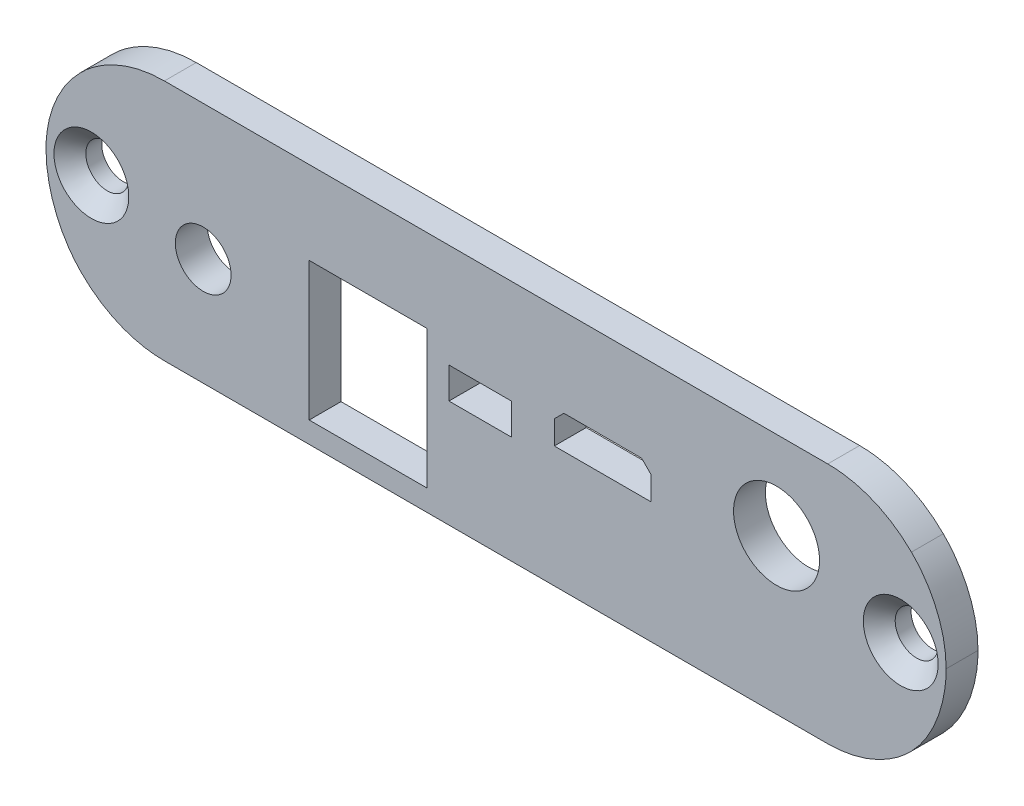
SolidWorks part; units mm, degrees
ref_plane "Front Plane" through (0, 0, 0) normal (0, 0, 1) x (1, 0, 0)
ref_plane "Top Plane" through (0, 0, 0) normal (0, 1, 0) x (1, 0, 0)
ref_plane "Right Plane" through (0, 0, 0) normal (1, 0, 0) x (0, 0, -1)
sketch "Sketch1" plane through (0, 0, 0) normal (0, 0, 1) x (1, 0, 0)
  line L0 (-34.8252, 0.5402) -> (-25.613, -10.3017) construction
  line L1 (-54.0003, -2.1716) -> (-52.2859, -2.1716) construction
  line L2 (-34.9181, 0.631) -> (-25.5201, 0.631)
  line L3 (-34.9181, 0.631) -> (-34.9181, -10.3925)
  line L4 (-34.9181, -10.3925) -> (-25.5201, -10.3925)
  line L5 (-25.5201, 0.631) -> (-25.5201, -10.3925)
  line L6 (-34.9181, 0.631) -> (-25.5201, -10.3925) construction
  line L7 (-34.9181, -10.3925) -> (-25.5201, 0.631) construction
  line L8 (-52.2859, -2.1716) -> (-52.2859, -3.886) construction
  line L9 (-45.5926, -3.5091) -> (-43.3701, -3.5091) construction
  line L10 (-43.3701, -3.5091) -> (-43.3701, -5.7317) construction
  line L11 (-1.0789, 0.25) -> (2.35, 0.25) construction
  line L12 (2.35, 0.25) -> (2.35, -3.1789) construction
  line L13 (10.541, -2.1716) -> (12.2554, -2.1716) construction
  line L14 (12.2554, -2.1716) -> (12.2554, -3.886) construction
  line L15 (-15.3715, -0.5328) -> (-14.6095, 0.2292)
  line L16 (-23.7738, -1.0201) -> (-18.7701, -1.0201)
  line L17 (-23.7738, -1.0201) -> (-23.7738, -3.5092)
  line L18 (-23.7738, -3.5092) -> (-18.7701, -3.5092)
  line L19 (-18.7701, -1.0201) -> (-18.7701, -3.5092)
  line L20 (-15.3715, -2.4124) -> (-7.6499, -2.4124)
  line L21 (-15.3715, -2.4124) -> (-15.3715, -0.5328)
  line L22 (-14.6095, 0.2292) -> (-8.4119, 0.2292)
  line L23 (-7.6499, -2.4124) -> (-7.6499, -0.5328)
  line L24 (-8.4119, 0.2292) -> (-7.6499, -0.5328)
  line L130 (-15.3715, -0.5123) -> (-15.3715, -2.4124) construction
  line L131 (-15.3715, -2.4124) -> (-7.6499, -2.4124) construction
  line L132 (-7.6499, -2.4124) -> (-7.6499, -0.5123) construction
  line L133 (-7.6499, -0.5123) -> (-8.4368, 0.2292) construction
  line L134 (-8.4368, 0.2292) -> (-14.5846, 0.2292) construction
  line L135 (-14.5846, 0.2292) -> (-15.3715, -0.5123) construction
  line L297 (-25.5201, 0.3213) -> (-25.5201, -10.0829) construction
  line L298 (-25.8376, -10.3926) -> (-34.6006, -10.3926) construction
  line L299 (-34.9181, -10.0829) -> (-34.9181, 0.3213) construction
  line L300 (-34.6006, 0.631) -> (-25.8376, 0.631) construction
  line L301 (-18.7701, -1.0201) -> (-18.7701, -3.5092) construction
  line L302 (-18.7701, -3.5092) -> (-23.7738, -3.5092) construction
  line L303 (-23.7738, -3.5092) -> (-23.7738, -1.0201) construction
  line L304 (-23.7738, -1.0201) -> (-18.7701, -1.0201) construction
  line L305 (6.434, 7.2517) -> (-46.4644, 7.2517)
  line L306 (-46.4644, -12.0777) -> (6.434, -12.0777)
  circle A0 centre (2.35, 0.25) radius 3.4289
  circle A1 centre (12.2554, -2.1716) radius 1.7144
  circle A2 centre (-43.3701, -3.5091) radius 2.2226
  circle A3 centre (-52.2859, -2.1716) radius 1.7144
  spline S469 degree 3 poles (-52.2858, -0.4572) (-51.339, -0.4572) (-50.5714, -1.2248) (-50.5714, -2.1716) knots 0 0 0 0 0.25 0.25 0.25 0.25 construction
  spline S470 degree 3 poles (-50.5714, -2.1716) (-50.5714, -3.1185) (-51.339, -3.8861) (-52.2859, -3.886) knots 0.25 0.25 0.25 0.25 0.5 0.5 0.5 0.5 construction
  spline S471 degree 3 poles (-52.2859, -3.886) (-53.2327, -3.886) (-54.0004, -3.1184) (-54.0003, -2.1716) knots 0.5 0.5 0.5 0.5 0.75 0.75 0.75 0.75 construction
  spline S472 degree 3 poles (-54.0003, -2.1716) (-54.0003, -1.2248) (-53.2327, -0.4571) (-52.2858, -0.4572) knots 0.75 0.75 0.75 0.75 1 1 1 1 construction
  spline S473 degree 3 poles (-43.37, -1.2867) (-42.1426, -1.2867) (-41.1474, -2.2817) (-41.1476, -3.5092) knots 0 0 0 0 0.25 0.25 0.25 0.25 construction
  spline S474 degree 3 poles (-41.1476, -3.5092) (-41.1476, -4.7366) (-42.1426, -5.7318) (-43.3701, -5.7317) knots 0.25 0.25 0.25 0.25 0.5 0.5 0.5 0.5 construction
  spline S475 degree 3 poles (-43.3701, -5.7317) (-44.5975, -5.7317) (-45.5927, -4.7366) (-45.5926, -3.5091) knots 0.5 0.5 0.5 0.5 0.75 0.75 0.75 0.75 construction
  spline S476 degree 3 poles (-45.5926, -3.5091) (-45.5926, -2.2817) (-44.5975, -1.2866) (-43.37, -1.2867) knots 0.75 0.75 0.75 0.75 1 1 1 1 construction
  spline S477 degree 3 poles (-25.5201, -10.0829) (-25.52, -10.1651) (-25.5534, -10.2435) (-25.613, -10.3017) knots 0.083333 0.083333 0.083333 0.083333 0.166667 0.166667 0.166667 0.166667 construction
  spline S478 degree 3 poles (-25.613, -10.3017) (-25.6725, -10.3598) (-25.7533, -10.3925) (-25.8376, -10.3926) knots 0.166667 0.166667 0.166667 0.166667 0.25 0.25 0.25 0.25 construction
  spline S479 degree 3 poles (-34.6006, -10.3926) (-34.6848, -10.3926) (-34.7653, -10.36) (-34.8249, -10.3019) knots 0.333333 0.333333 0.333333 0.333333 0.416667 0.416667 0.416667 0.416667 construction
  spline S480 degree 3 poles (-34.8249, -10.3019) (-34.8845, -10.2439) (-34.918, -10.1651) (-34.9181, -10.0829) knots 0.416667 0.416667 0.416667 0.416667 0.5 0.5 0.5 0.5 construction
  spline S481 degree 3 poles (-34.9181, 0.3213) (-34.9181, 0.4036) (-34.8847, 0.482) (-34.8252, 0.5402) knots 0.583333 0.583333 0.583333 0.583333 0.666667 0.666667 0.666667 0.666667 construction
  spline S482 degree 3 poles (-34.8252, 0.5402) (-34.7656, 0.5983) (-34.6848, 0.631) (-34.6006, 0.631) knots 0.666667 0.666667 0.666667 0.666667 0.75 0.75 0.75 0.75 construction
  spline S483 degree 3 poles (-25.8376, 0.631) (-25.7533, 0.6311) (-25.6729, 0.5985) (-25.6133, 0.5404) knots 0.833333 0.833333 0.833333 0.833333 0.916667 0.916667 0.916667 0.916667 construction
  spline S484 degree 3 poles (-25.6133, 0.5404) (-25.5537, 0.4824) (-25.5201, 0.4036) (-25.5201, 0.3213) knots 0.916667 0.916667 0.916667 0.916667 1 1 1 1 construction
  spline S485 degree 3 poles (12.2555, -0.4572) (13.2023, -0.4572) (13.9699, -1.2248) (13.9699, -2.1716) knots 0 0 0 0 0.25 0.25 0.25 0.25 construction
  spline S486 degree 3 poles (13.9699, -2.1716) (13.9699, -3.1185) (13.2023, -3.8861) (12.2554, -3.886) knots 0.25 0.25 0.25 0.25 0.5 0.5 0.5 0.5 construction
  spline S487 degree 3 poles (12.2554, -3.886) (11.3086, -3.886) (10.5409, -3.1184) (10.541, -2.1716) knots 0.5 0.5 0.5 0.5 0.75 0.75 0.75 0.75 construction
  spline S488 degree 3 poles (10.541, -2.1716) (10.541, -1.2248) (11.3086, -0.4571) (12.2555, -0.4572) knots 0.75 0.75 0.75 0.75 1 1 1 1 construction
  spline S489 degree 3 poles (2.3501, 3.6789) (4.2438, 3.6789) (5.779, 2.1437) (5.779, 0.2499) knots 0 0 0 0 0.25 0.25 0.25 0.25 construction
  spline S490 degree 3 poles (5.779, 0.2499) (5.779, -1.6439) (4.2438, -3.179) (2.35, -3.1789) knots 0.25 0.25 0.25 0.25 0.5 0.5 0.5 0.5 construction
  spline S491 degree 3 poles (2.35, -3.1789) (0.4563, -3.1789) (-1.079, -1.6438) (-1.0789, 0.25) knots 0.5 0.5 0.5 0.5 0.75 0.75 0.75 0.75 construction
  spline S492 degree 3 poles (-1.0789, 0.25) (-1.0789, 2.1437) (0.4563, 3.679) (2.3501, 3.6789) knots 0.75 0.75 0.75 0.75 1 1 1 1 construction
  spline S493 degree 3 poles (15.875, -2.1771) (15.8735, 0.3223) (14.8775, 2.7305) (13.1074, 4.496) knots 0 0 0 0 0.1 0.1 0.1 0.1
  spline S494 degree 3 poles (13.1074, 4.496) (11.3364, 6.2625) (8.9354, 7.2533) (6.434, 7.2517) knots 0.1 0.1 0.1 0.1 0.2 0.2 0.2 0.2
  spline S495 degree 3 poles (-46.4644, 7.2517) (-48.9654, 7.2501) (-51.3771, 6.2567) (-53.1462, 4.4876) knots 0.3 0.3 0.3 0.3 0.4 0.4 0.4 0.4
  spline S496 degree 3 poles (-53.1462, 4.4876) (-54.9139, 2.7201) (-55.907, 0.3228) (-55.9054, -2.1769) knots 0.4 0.4 0.4 0.4 0.5 0.5 0.5 0.5
  spline S497 degree 3 poles (-55.9054, -2.1769) (-55.9039, -4.7242) (-54.9188, -7.4291) (-53.137, -9.2518) knots 0.5 0.5 0.5 0.5 0.6 0.6 0.6 0.6
  spline S498 degree 3 poles (-53.137, -9.2518) (-51.3786, -11.0507) (-48.9824, -12.0793) (-46.4644, -12.0777) knots 0.6 0.6 0.6 0.6 0.7 0.7 0.7 0.7
  spline S499 degree 3 poles (6.434, -12.0777) (8.9516, -12.0761) (11.3581, -11.0449) (13.1151, -9.2429) knots 0.8 0.8 0.8 0.8 0.9 0.9 0.9 0.9
  spline S500 degree 3 poles (13.1151, -9.2429) (14.8954, -7.4173) (15.8766, -4.7239) (15.875, -2.1771) knots 0.9 0.9 0.9 0.9 1 1 1 1
  point P0 (-30.2191, -4.8807)
  point P9 (-7.6499, 0.2292)
  point P10 (-15.3715, 0.2292)
extrude "Boss-Extrude1" add sketch "Sketch1" along normal blind 2.54
chamfer "Chamfer1" distance 1.27 angle 45 2 edges at (13.9698, -2.1716, 2.54) (-50.5715, -2.1716, 2.54)
